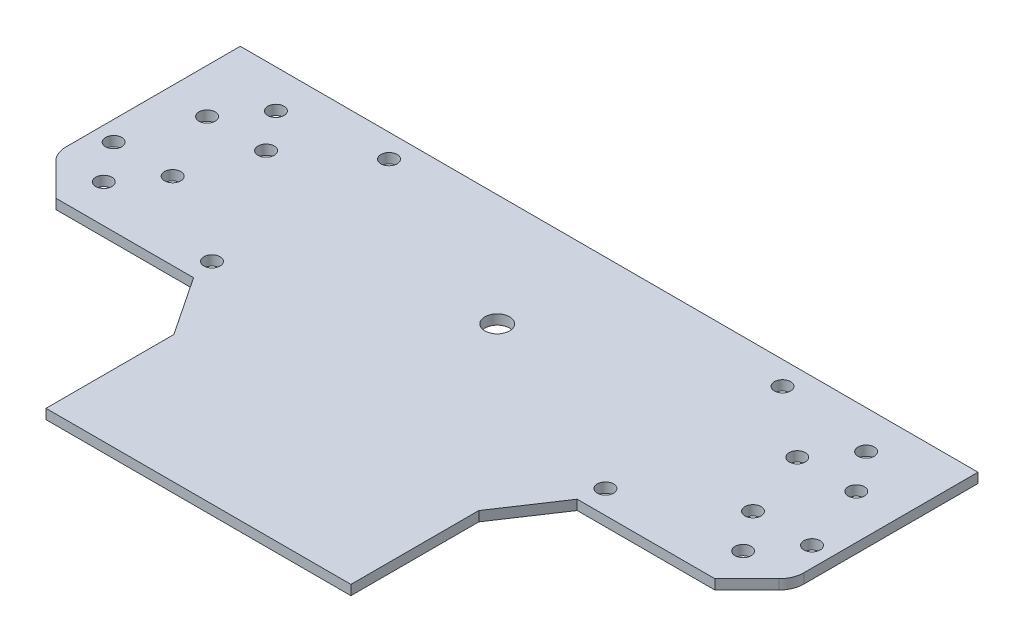
SolidWorks part; units mm, degrees
ref_plane "前视基准面" through (0, 0, 0) normal (0, 0, 1) x (1, 0, 0)
ref_plane "上视基准面" through (0, 0, 0) normal (0, 1, 0) x (1, 0, 0)
ref_plane "右视基准面" through (0, 0, 0) normal (1, 0, 0) x (0, 0, -1)
sketch "草图1" plane through (0, 0, 0) normal (0, 1, 0) x (1, 0, 0)
  line L1 (-75, -22.75) -> (75, -22.75)
  line L2 (-75, -22.75) -> (-75, 22.75)
  line L3 (-75, 22.75) -> (75, 22.75)
  line L4 (75, -22.75) -> (75, 22.75)
  line L5 (-75, -22.75) -> (75, 22.75) construction
  line L6 (-75, 22.75) -> (75, -22.75) construction
  point P0 (0, 0)
  dimension "D1" = 45.5
  dimension "D2" = 150
extrude "凸台-拉伸1" add sketch "草图1" along normal blind 2
sketch "草图2" plane through (0, 2, 0) normal (0, 1, 0) x (1, 0, 0)
  line L0 (-60, -11) -> (-65, -11) construction
  line L1 (-60, -11) -> (60, -11) construction
  line L2 (-60, -11) -> (-60, 11) construction
  line L3 (-60, 11) -> (60, 11) construction
  line L4 (60, -11) -> (60, 11) construction
  line L5 (-60, -11) -> (60, 11) construction
  line L6 (-60, 11) -> (60, -11) construction
  line L12 (-66, 7) -> (-54, 7) construction
  line L13 (-71, -15) -> (-59, -15) construction
  line L14 (-66, 7) -> (-66, 15) construction
  line L15 (-66, 15) -> (-54, 15) construction
  line L16 (-54, 7) -> (-54, 15) construction
  line L17 (-66, 7) -> (-54, 15) construction
  line L18 (-66, 15) -> (-54, 7) construction
  line L19 (-71, -15) -> (-71, -7) construction
  line L20 (-71, -7) -> (-59, -7) construction
  line L21 (-59, -15) -> (-59, -7) construction
  line L22 (-71, -15) -> (-59, -7) construction
  line L23 (-71, -7) -> (-59, -15) construction
  circle A4 centre (-60, 15) radius 1.65
  circle A5 centre (-66, 7) radius 1.65
  circle A6 centre (-54, 7) radius 1.65
  circle A7 centre (-71, -7) radius 1.65
  circle A8 centre (-59, -7) radius 1.65
  circle A9 centre (-65, -15) radius 1.65
  point P0 (0, 0)
  point P14 (-60, 0)
  dimension "D5" = 3.3
  dimension "D1" = 12
  dimension "D2" = 8
  dimension "D3" = 15
  dimension "D4" = 120
  dimension "D6" = 5
  dimension "D7" = 8
  dimension "D8" = 12
extrude "切除-拉伸1" cut sketch "草图2" against normal up to next
mirror "镜向1" about plane through (0, 0, 0) normal (1, 0, 0) of "切除-拉伸1"
chamfer "倒角1" distance 8 angle 45 2 edges at (75, 1, 22.75) (-75, 1, 22.75)
sketch "草图3" plane through (0, 2, 0) normal (0, 1, 0) x (1, 0, 0)
  circle A0 centre (0, 0) radius 2.5
  dimension "D1" = 5
extrude "临时配合孔" cut sketch "草图3" against normal up to next
sketch "草图4" plane through (0, 2, 0) normal (0, 1, 0) x (1, 0, 0)
  line L1 (-40, -18) -> (40, -18) construction
  line L2 (-40, -18) -> (-40, 18) construction
  line L3 (-40, 18) -> (40, 18) construction
  line L4 (40, -18) -> (40, 18) construction
  line L5 (-40, -18) -> (40, 18) construction
  line L6 (-40, 18) -> (40, -18) construction
  circle A0 centre (-40, 18) radius 1.65
  circle A1 centre (-40, -18) radius 1.65
  circle A2 centre (40, 18) radius 1.65
  circle A3 centre (40, -18) radius 1.65
  point P0 (0, 0)
  dimension "D3" = 3.3
  dimension "D1" = 36
  dimension "D2" = 80
extrude "切除-拉伸2" cut sketch "草图4" against normal up to next
fillet "圆角1" radius 5 2 edges at (75, 1, 14.75) (-75, 1, 14.75)
sketch "草图5" plane through (0, 0, 0) normal (0, 1, 0) x (1, 0, 0)
  line L0 (0, 0) -> (0, -41.75) construction
  line L1 (-67, -22.75) -> (67, -22.75) construction
  line L2 (-31, -60.75) -> (31, -60.75)
  line L3 (-31, -60.75) -> (-31, -22.75)
  line L4 (-31, -22.75) -> (31, -22.75)
  line L5 (31, -60.75) -> (31, -22.75)
  line L6 (-31, -60.75) -> (31, -22.75) construction
  line L7 (-31, -22.75) -> (31, -60.75) construction
  dimension "D1" = 62
  dimension "D2" = 38
extrude "凸台-拉伸2" add sketch "草图5" along normal up to surface (2 mm away) up to face at (-40, 2, 19.65)
sketch "草图6" plane through (0, 0, 0) normal (0, 1, 0) x (1, 0, 0)
  line L0 (-31, -22.75) -> (-31, -34.75)
  line L1 (-31, -60.75) -> (-31, -22.75) construction
  line L2 (-31, -34.75) -> (-39, -22.75)
  line L3 (-67, -22.75) -> (-31, -22.75) construction
  line L4 (-39, -22.75) -> (-31, -22.75)
  line L5 (31, -22.75) -> (31, -34.75)
  line L6 (31, -22.75) -> (31, -60.75) construction
  line L7 (31, -34.75) -> (39, -22.75)
  line L8 (31, -22.75) -> (67, -22.75) construction
  line L9 (39, -22.75) -> (31, -22.75)
  line L10 (-31, -34.75) -> (31, -34.75) construction
  dimension "D1" = 8
  dimension "D2" = 12
extrude "凸台-拉伸3" add sketch "草图6" along normal up to surface (2 mm away) up to face at (-40, 2, 19.65)
